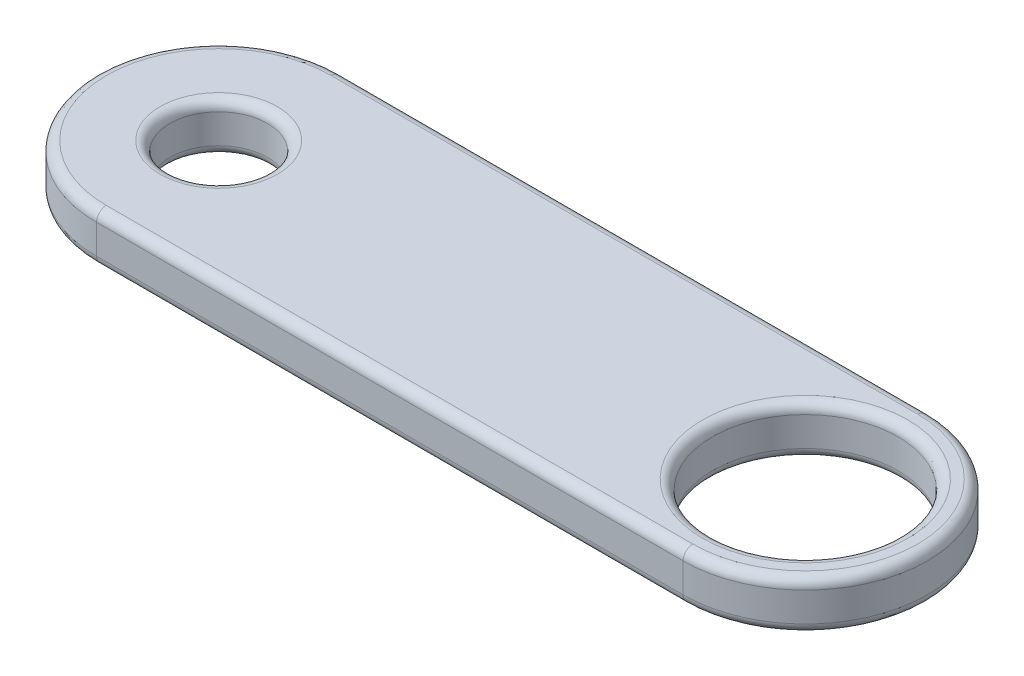
SolidWorks part; units mm, degrees
ref_plane "Front Plane" through (0, 0, 0) normal (0, 0, 1) x (1, 0, 0)
ref_plane "Top Plane" through (0, 0, 0) normal (0, 1, 0) x (1, 0, 0)
ref_plane "Right Plane" through (0, 0, 0) normal (1, 0, 0) x (0, 0, -1)
sketch "Sketch1" plane through (0, 0, 0) normal (0, 1, 0) x (1, 0, 0)
  line L0 (0, 12.5) -> (60, 12.5)
  line L1 (0, -12.5) -> (60, -12.5)
  arc A0 (0, 12.5) -> (0, -12.5) centre (0, 0) ccw
  arc A1 (60, -12.5) -> (60, 12.5) centre (60, 0) ccw
  circle A2 centre (0, 0) radius 5
  circle A3 centre (60, 0) radius 9.5
  dimension "D1" = 25
  dimension "D2" = 25
  dimension "D4" = 10
  dimension "D5" = 19
  dimension "D3" = 60
extrude "Boss-Extrude1" add sketch "Sketch1" along normal mid plane 5
fillet "Fillet1" radius 1 12 edges at (60, -2.5, 9.5) (0, -2.5, 5) (30, -2.5, 12.5) (72.5, -2.5, 0) (30, -2.5, -12.5) (-12.5, -2.5, 0) (60, 2.5, 9.5) (30, 2.5, -12.5) (72.5, 2.5, 0) (30, 2.5, 12.5) (-12.5, 2.5, 0) (0, 2.5, 5)
